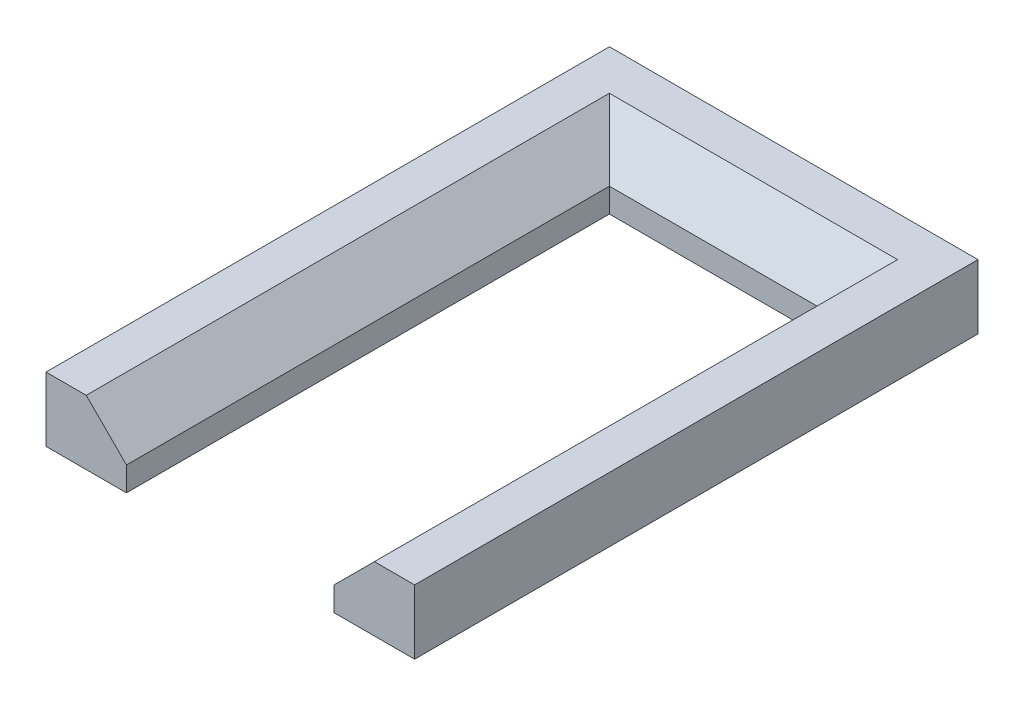
SolidWorks part; units mm, degrees
ref_plane "Front Plane" through (0, 0, 0) normal (0, 0, 1) x (1, 0, 0)
ref_plane "Top Plane" through (0, 0, 0) normal (0, 1, 0) x (1, 0, 0)
ref_plane "Right Plane" through (0, 0, 0) normal (1, 0, 0) x (0, 0, -1)
sketch "Sketch1" plane through (0, 0, 0) normal (0, 1, 0) x (1, 0, 0)
  line L0 (-22.9, 0) -> (-12.9, 0)
  line L1 (-12.9, 0) -> (-12.9, 60)
  line L2 (-12.9, 60) -> (12.9, 60)
  line L3 (12.9, 60) -> (12.9, 0)
  line L4 (12.9, 0) -> (22.9, 0)
  line L5 (22.9, 0) -> (22.9, 70)
  line L6 (22.9, 70) -> (-22.9, 70)
  line L7 (-22.9, 70) -> (-22.9, 0)
  dimension "D1" = 25.8
  dimension "D2" = 60
  dimension "D3" = 70
  dimension "D4" = 12.9
  dimension "D5" = 10
  dimension "D6" = 10
extrude "Boss-Extrude1" add sketch "Sketch1" along normal blind 8
chamfer "Chamfer1" distance 5 angle 45 3 edges at (-12.9, 8, -30) (0, 8, -60) (12.9, 8, -30)
